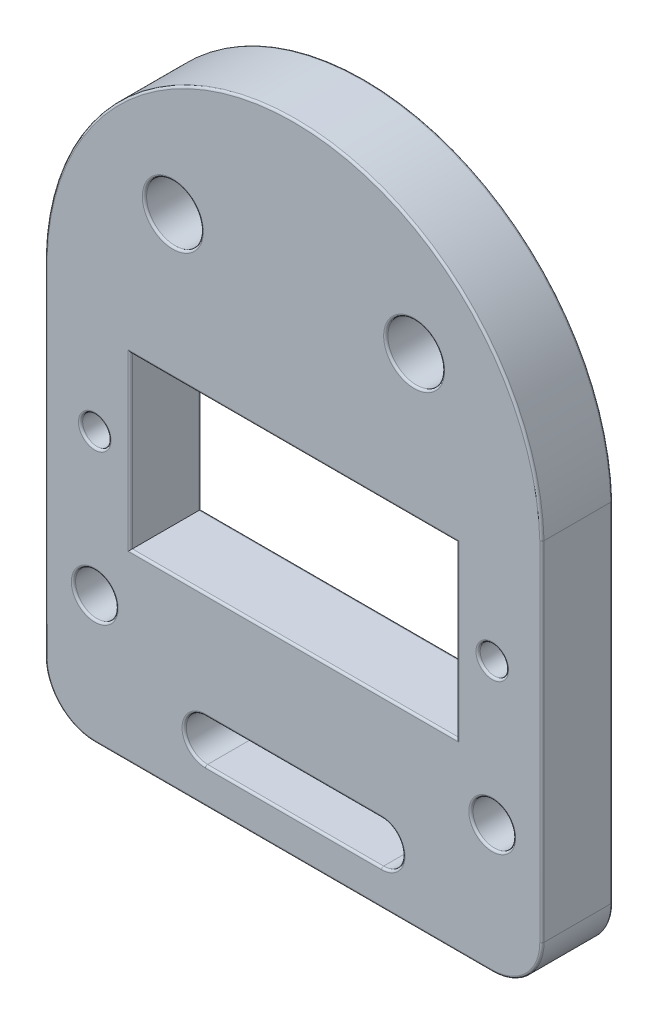
SolidWorks part; units mm, degrees
ref_plane "前视基准面" through (0, 0, 0) normal (0, 0, 1) x (1, 0, 0)
ref_plane "上视基准面" through (0, 0, 0) normal (0, 1, 0) x (1, 0, 0)
ref_plane "右视基准面" through (0, 0, 0) normal (1, 0, 0) x (0, 0, -1)
sketch "草图1" plane through (0, 0, 0) normal (0, 0, 1) x (1, 0, 0)
  line L0 (0, 0) -> (0, 26) construction
  line L1 (-11.5, -6) -> (11.5, -6)
  line L2 (-11.5, -6) -> (-11.5, 6)
  line L3 (-11.5, 6) -> (11.5, 6)
  line L4 (11.5, -6) -> (11.5, 6)
  line L5 (-11.5, -6) -> (11.5, 6) construction
  line L6 (-11.5, 6) -> (11.5, -6) construction
  line L7 (0, 0) -> (0, -19) construction
  line L8 (0, -19) -> (25.8504, -19)
  line L9 (-6.2, -15) -> (6.2, -15) construction
  line L10 (-6.2, -13.5) -> (6.2, -13.5)
  line L11 (-6.2, -16.5) -> (6.2, -16.5)
  line L13 (-17.5, 9) -> (17.5, 9) construction
  line L14 (-17.5, 9) -> (-17.5, -19)
  line L15 (-17.5, -19) -> (17.5, -19)
  line L16 (17.5, 9) -> (17.5, -19)
  circle A0 centre (-14, 0) radius 1
  circle A1 centre (-14, -10) radius 1.5
  arc A2 (-6.2, -13.5) -> (-6.2, -16.5) centre (-6.2, -15) ccw
  arc A3 (6.2, -16.5) -> (6.2, -13.5) centre (6.2, -15) ccw
  circle A4 centre (-8.5, 16) radius 2
  circle A5 centre (14, -10) radius 1.5
  circle A6 centre (14, 0) radius 1
  circle A7 centre (8.5, 16) radius 2
  arc A8 (-17.5, 9) -> (17.5, 9) centre (0, 8.4926) cw
  point P0 (0, 0)
  point P16 (0, -15)
  point P27 (0, -19)
  dimension "D3" = 2
  dimension "D6" = 3
  dimension "D10" = 1.5
  dimension "D11" = 4
  dimension "D1" = 23
  dimension "D2" = 12
  dimension "D4" = 2.5
  dimension "D5" = 13
  dimension "D7" = 10
  dimension "D8" = 4
  dimension "D9" = 12.4
  dimension "D12" = 10
  dimension "D13" = 8.5
  dimension "D14" = 45
  dimension "D15" = 28
  dimension "D16" = 35
extrude "凸台-拉伸1" add sketch "草图1" along normal blind 5 contours A8 L14 L15 L8 L16 A6 L4 L1 L2 L3 A0 A1 A3 L11 A2 L10 A4 A5 A7
fillet "圆角1" radius 3.5 2 edges at (-17.5, -19, 2.5) (17.5, -19, 2.5)
fillet "圆角2" radius 0.15 40 edges at (10.5, 16, 0) (15.5, -10, 0) (-6.5, 16, 0) (0, -16.5, 0) (-7.7, -15, 0) (0, -13.5, 0) (7.7, -15, 0) (-12.5, -10, 0) (-13, 0, 0) (0, -6, 0) (-11.5, 0, 0) (0, 6, 0) (11.5, 0, 0) (15, 0, 0) (16.4749, -17.9749, 0) (17.5, -3.25, 0) (0, 26, 0) (-17.5, -3.25, 0) (-16.4749, -17.9749, 0) (0, -19, 0) (10.5, 16, 5) (15.5, -10, 5) (-6.5, 16, 5) (0, -13.5, 5) (-7.7, -15, 5) (0, -16.5, 5) (7.7, -15, 5) (-12.5, -10, 5) (-13, 0, 5) (0, 6, 5) (-11.5, 0, 5) (0, -6, 5) (11.5, 0, 5) (15, 0, 5) (0, 26, 5) (17.5, -3.25, 5) (16.4749, -17.9749, 5) (0, -19, 5) (-16.4749, -17.9749, 5) (-17.5, -3.25, 5)
